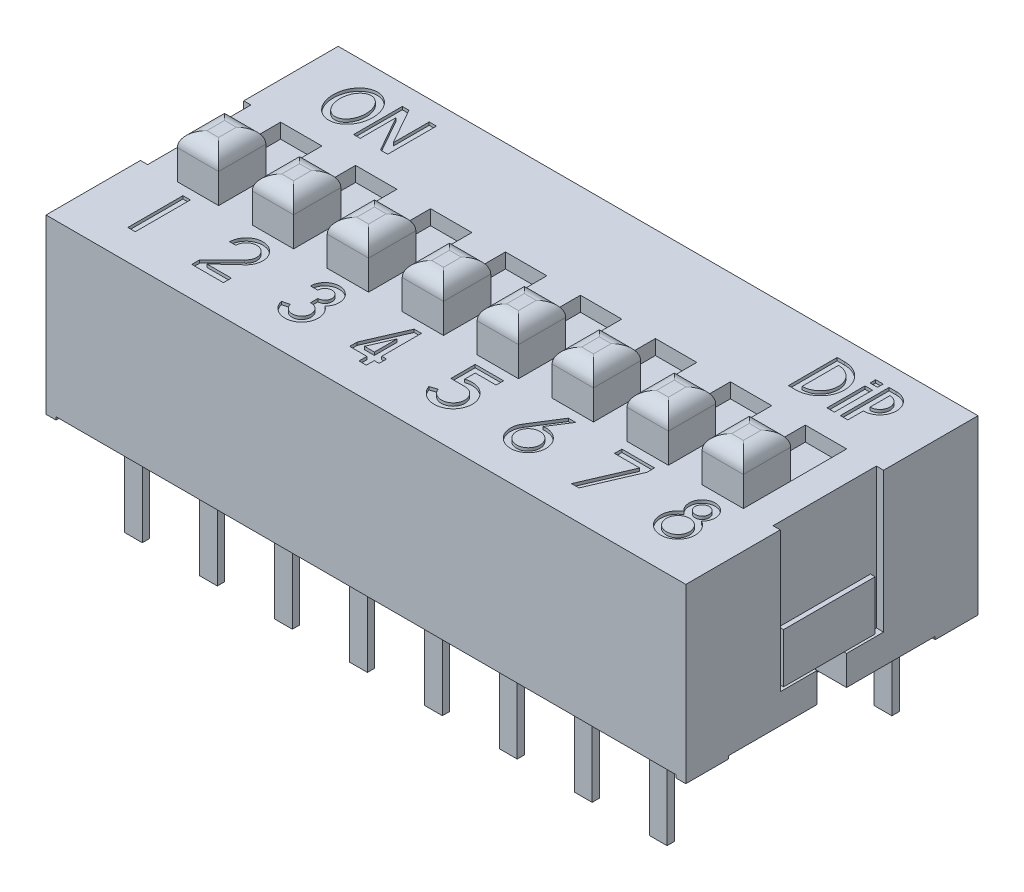
SolidWorks part; units mm, degrees
ref_plane "Front Plane" through (0, 0, 0) normal (0, 0, 1) x (1, 0, 0)
ref_plane "Top Plane" through (0, 0, 0) normal (0, 1, 0) x (1, 0, 0)
ref_plane "Right Plane" through (0, 0, 0) normal (1, 0, 0) x (0, 0, -1)
sketch "Sketch3" plane through (0, 0, 0) normal (0, 1, 0) x (1, 0, 0)
  line L1 (-10.84, 4.95) -> (10.84, 4.95)
  line L2 (-10.84, 4.95) -> (-10.84, -4.95)
  line L3 (-10.84, -4.95) -> (10.84, -4.95)
  line L4 (10.84, 4.95) -> (10.84, -4.95)
  line L5 (-10.84, 4.95) -> (10.84, -4.95) construction
  line L6 (-10.84, -4.95) -> (10.84, 4.95) construction
  point P0 (0, 0)
  dimension "D1" = 21.68
  dimension "D2" = 9.9
extrude "Boss-Extrude2" add sketch "Sketch3" against normal blind 5.85
sketch "Sketch4" plane through (0, 0, 4.95) normal (0, 0, 1) x (1, 0, 0)
  line L0 (-10.84, -5.85) -> (10.84, -5.85) construction
  line L1 (-10.5, -5.75) -> (10.5, -5.75)
  line L2 (-10.5, -5.75) -> (-10.5, -5.95)
  line L3 (-10.5, -5.95) -> (10.5, -5.95)
  line L4 (10.5, -5.75) -> (10.5, -5.95)
  line L5 (-10.5, -5.75) -> (10.5, -5.95) construction
  line L6 (-10.5, -5.95) -> (10.5, -5.75) construction
  point P0 (0, -5.85)
  dimension "D1" = 0.2
  dimension "D2" = 21
extrude "Cut-Extrude2" cut sketch "Sketch4" against normal blind 10
sketch "Sketch5" plane through (-10.84, 0, 0) normal (-1, 0, 0) x (0, 0, 1)
  line L0 (-4.95, -5.85) -> (4.95, -5.85) construction
  line L1 (-3.5, -5.75) -> (3.5, -5.75)
  line L2 (-3.5, -5.75) -> (-3.5, -5.95)
  line L3 (-3.5, -5.95) -> (3.5, -5.95)
  line L4 (3.5, -5.75) -> (3.5, -5.95)
  line L5 (-3.5, -5.75) -> (3.5, -5.95) construction
  line L6 (-3.5, -5.95) -> (3.5, -5.75) construction
  point P0 (0, -5.85)
  dimension "D1" = 0.2
  dimension "D2" = 7
extrude "Cut-Extrude3" cut sketch "Sketch5" against normal blind 22
sketch "Sketch6" plane through (0, 0, 0) normal (0, 1, 0) x (1, 0, 0)
  line L0 (-10.84, 4.95) -> (-10.84, -4.95) construction
  line L1 (-11.0837, 1.75) -> (-10.5963, 1.75)
  line L2 (-11.0837, 1.75) -> (-11.0837, -1.75)
  line L3 (-11.0837, -1.75) -> (-10.5963, -1.75)
  line L4 (-10.5963, 1.75) -> (-10.5963, -1.75)
  line L5 (-11.0837, 1.75) -> (-10.5963, -1.75) construction
  line L6 (-11.0837, -1.75) -> (-10.5963, 1.75) construction
  line L7 (0, 4.95) -> (0, -4.95) construction
  line L8 (10.84, 4.95) -> (-10.84, 4.95) construction
  line L9 (-10.84, -4.95) -> (10.84, -4.95) construction
  line L10 (11.0837, -1.75) -> (10.5963, 1.75) construction
  line L11 (11.0837, 1.75) -> (10.5963, -1.75) construction
  line L12 (10.5963, 1.75) -> (10.5963, -1.75)
  line L13 (11.0837, -1.75) -> (10.5963, -1.75)
  line L14 (11.0837, 1.75) -> (11.0837, -1.75)
  line L15 (11.0837, 1.75) -> (10.5963, 1.75)
  point P0 (-10.84, 0)
  point P17 (10.84, 0)
  dimension "D1" = 3.5
extrude "Cut-Extrude4" cut sketch "Sketch6" against normal blind 4.75
sketch "Sketch7" plane through (-10.84, 0, 0) normal (-1, 0, 0) x (0, 0, 1)
  line L0 (1.75, -4.75) -> (-1.75, -4.75) construction
  line L1 (0.4994, -4.75) -> (-0.4963, -4.75)
  line L2 (0.4994, -4.75) -> (0.4994, -5.75)
  line L3 (0.4994, -5.75) -> (-0.4963, -5.75)
  line L4 (-0.4963, -4.75) -> (-0.4963, -5.75)
  line L5 (3.5, -5.75) -> (-3.5, -5.75) construction
extrude "Cut-Extrude5" cut sketch "Sketch7" against normal blind 22
sketch "Sketch8" plane through (-10.5963, 0, 0) normal (-1, 0, 0) x (0, 0, 1)
  line L0 (1.75, -4.75) -> (0.4994, -4.75) construction
  line L1 (1.55, -4.75) -> (-1.55, -4.75)
  line L2 (1.55, -4.75) -> (1.55, -3.0694)
  line L3 (1.55, -3.0694) -> (-1.55, -3.0694)
  line L4 (-1.55, -4.75) -> (-1.55, -3.0694)
  line L5 (-1.75, 0) -> (-1.75, -4.75) construction
  line L6 (1.75, -4.75) -> (1.75, 0) construction
  dimension "D1" = 0.2
  dimension "D2" = 0.2
extrude "Boss-Extrude3" add sketch "Sketch8" along normal blind 0.15 and the other way blind 21.35
sketch "Sketch9" plane through (0, 0, 0) normal (0, 1, 0) x (1, 0, 0)
  line L0 (-10.84, 4.95) -> (-10.84, 1.75) construction
  line L1 (-9.59, 1.75) -> (-8.19, 1.75)
  line L2 (-9.59, 1.75) -> (-9.59, -1.75)
  line L3 (-9.59, -1.75) -> (-8.19, -1.75)
  line L4 (-8.19, 1.75) -> (-8.19, -1.75)
  line L5 (-9.59, 1.75) -> (-8.19, -1.75) construction
  line L6 (-9.59, -1.75) -> (-8.19, 1.75) construction
  line L7 (0, 4.95) -> (0, -4.95) construction
  line L8 (-7.0506, 1.75) -> (-5.6494, 1.75)
  line L9 (-7.0506, 1.75) -> (-7.0506, -1.75)
  line L10 (-7.0506, -1.75) -> (-5.6494, -1.75)
  line L11 (-5.6494, 1.75) -> (-5.6494, -1.75)
  line L12 (-7.0506, 1.75) -> (-5.6494, -1.75) construction
  line L13 (-7.0506, -1.75) -> (-5.6494, 1.75) construction
  line L14 (-4.5106, 1.75) -> (-3.1094, 1.75)
  line L15 (-4.5106, 1.75) -> (-4.5106, -1.75)
  line L16 (-4.5106, -1.75) -> (-3.1094, -1.75)
  line L17 (-3.1094, 1.75) -> (-3.1094, -1.75)
  line L18 (-4.5106, 1.75) -> (-3.1094, -1.75) construction
  line L19 (-4.5106, -1.75) -> (-3.1094, 1.75) construction
  line L20 (-1.9706, 1.75) -> (-0.5694, 1.75)
  line L21 (-1.9706, 1.75) -> (-1.9706, -1.75)
  line L22 (-1.9706, -1.75) -> (-0.5694, -1.75)
  line L23 (-0.5694, 1.75) -> (-0.5694, -1.75)
  line L24 (-1.9706, 1.75) -> (-0.5694, -1.75) construction
  line L25 (-1.9706, -1.75) -> (-0.5694, 1.75) construction
  line L26 (10.84, 4.95) -> (-10.84, 4.95) construction
  line L27 (-10.84, -4.95) -> (10.84, -4.95) construction
  line L28 (1.9706, -1.75) -> (0.5694, 1.75) construction
  line L29 (1.9706, 1.75) -> (0.5694, -1.75) construction
  line L30 (4.5106, -1.75) -> (3.1094, 1.75) construction
  line L31 (4.5106, 1.75) -> (3.1094, -1.75) construction
  line L32 (7.0506, -1.75) -> (5.6494, 1.75) construction
  line L33 (7.0506, 1.75) -> (5.6494, -1.75) construction
  line L34 (9.59, -1.75) -> (8.19, 1.75) construction
  line L35 (9.59, 1.75) -> (8.19, -1.75) construction
  line L36 (0.5694, 1.75) -> (0.5694, -1.75)
  line L37 (1.9706, -1.75) -> (0.5694, -1.75)
  line L38 (1.9706, 1.75) -> (1.9706, -1.75)
  line L39 (1.9706, 1.75) -> (0.5694, 1.75)
  line L40 (3.1094, 1.75) -> (3.1094, -1.75)
  line L41 (4.5106, -1.75) -> (3.1094, -1.75)
  line L42 (4.5106, 1.75) -> (4.5106, -1.75)
  line L43 (4.5106, 1.75) -> (3.1094, 1.75)
  line L44 (5.6494, 1.75) -> (5.6494, -1.75)
  line L45 (7.0506, -1.75) -> (5.6494, -1.75)
  line L46 (7.0506, 1.75) -> (7.0506, -1.75)
  line L47 (7.0506, 1.75) -> (5.6494, 1.75)
  line L48 (8.19, 1.75) -> (8.19, -1.75)
  line L49 (9.59, -1.75) -> (8.19, -1.75)
  line L50 (9.59, 1.75) -> (9.59, -1.75)
  line L51 (9.59, 1.75) -> (8.19, 1.75)
  point P0 (-8.89, 0)
  point P7 (-6.35, 0)
  point P13 (-3.81, 0)
  point P18 (-1.27, 0)
  point P45 (1.27, 0)
  point P46 (3.81, 0)
  point P47 (6.35, 0)
  point P48 (8.89, 0)
  dimension "D1" = 1.4
  dimension "D2" = 3.5
  dimension "D3" = 1.95
  dimension "D4" = 2.54
  dimension "D5" = 2.54
  dimension "D6" = 2.54
extrude "Cut-Extrude6" cut sketch "Sketch9" against normal blind 0.5
sketch "Sketch12" plane through (0, -0.5, 0) normal (0, 1, 0) x (1, 0, 0)
  line L0 (-9.59, 1.75) -> (-9.59, -1.75) construction
  line L1 (-8.19, -1.75) -> (-9.59, -1.75)
  line L2 (-8.19, -1.75) -> (-8.19, -0.15)
  line L3 (-8.19, -0.15) -> (-9.59, -0.15)
  line L4 (-9.59, -1.75) -> (-9.59, -0.15)
  line L5 (-7.0506, 1.75) -> (-7.0506, -1.75) construction
  line L6 (-5.6494, -1.75) -> (-7.0506, -1.75)
  line L7 (-5.6494, -1.75) -> (-5.6494, -0.15)
  line L8 (-5.6494, -0.15) -> (-7.0506, -0.15)
  line L9 (-7.0506, -1.75) -> (-7.0506, -0.15)
  line L10 (-4.5106, 1.75) -> (-4.5106, -1.75) construction
  line L11 (-3.1094, -1.75) -> (-4.5106, -1.75)
  line L12 (-3.1094, -1.75) -> (-3.1094, -0.15)
  line L13 (-3.1094, -0.15) -> (-4.5106, -0.15)
  line L14 (-4.5106, -1.75) -> (-4.5106, -0.15)
  line L15 (-1.9706, 1.75) -> (-1.9706, -1.75) construction
  line L16 (-1.9706, -0.15) -> (-0.5694, -0.15)
  line L17 (-1.9706, -0.15) -> (-1.9706, -1.75)
  line L18 (-1.9706, -1.75) -> (-0.5694, -1.75)
  line L19 (-0.5694, -0.15) -> (-0.5694, -1.75)
  line L20 (0.5694, 1.75) -> (0.5694, -1.75) construction
  line L21 (1.9706, -1.75) -> (0.5694, -1.75)
  line L22 (1.9706, -1.75) -> (1.9706, -0.15)
  line L23 (1.9706, -0.15) -> (0.5694, -0.15)
  line L24 (0.5694, -1.75) -> (0.5694, -0.15)
  line L25 (3.1094, 1.75) -> (3.1094, -1.75) construction
  line L26 (4.5106, -1.75) -> (3.1094, -1.75)
  line L27 (4.5106, -1.75) -> (4.5106, -0.15)
  line L28 (4.5106, -0.15) -> (3.1094, -0.15)
  line L29 (3.1094, -1.75) -> (3.1094, -0.15)
  line L30 (5.6494, 1.75) -> (5.6494, -1.75) construction
  line L31 (7.0506, -1.75) -> (5.6494, -1.75)
  line L32 (7.0506, -1.75) -> (7.0506, -0.15)
  line L33 (7.0506, -0.15) -> (5.6494, -0.15)
  line L34 (5.6494, -1.75) -> (5.6494, -0.15)
  line L35 (8.19, 1.75) -> (8.19, -1.75) construction
  line L36 (9.59, -1.75) -> (8.19, -1.75)
  line L37 (9.59, -1.75) -> (9.59, -0.15)
  line L38 (9.59, -0.15) -> (8.19, -0.15)
  line L39 (8.19, -1.75) -> (8.19, -0.15)
  dimension "D1" = 1.6
extrude "Boss-Extrude4" add sketch "Sketch12" along normal blind 2
fillet "Fillet1" radius 0.5 32 edges at (8.89, 1.5, 1.75) (8.19, 1.5, 0.95) (8.89, 1.5, 0.15) (9.59, 1.5, 0.95) (6.35, 1.5, 1.75) (5.6494, 1.5, 0.95) (6.35, 1.5, 0.15) (7.0506, 1.5, 0.95) (3.81, 1.5, 1.75) (3.1094, 1.5, 0.95) (3.81, 1.5, 0.15) (4.5106, 1.5, 0.95) (1.27, 1.5, 1.75) (0.5694, 1.5, 0.95) (1.27, 1.5, 0.15) (1.9706, 1.5, 0.95) (-1.27, 1.5, 0.15) (-0.5694, 1.5, 0.95) (-1.27, 1.5, 1.75) (-1.9706, 1.5, 0.95) (-3.81, 1.5, 1.75) (-4.5106, 1.5, 0.95) (-3.81, 1.5, 0.15) (-3.1094, 1.5, 0.95) (-6.35, 1.5, 1.75) (-7.0506, 1.5, 0.95) (-6.35, 1.5, 0.15) (-5.6494, 1.5, 0.95) (-8.89, 1.5, 1.75) (-9.59, 1.5, 0.95) (-8.89, 1.5, 0.15) (-8.19, 1.5, 0.95)
sketch "Sketch13" plane through (0, -5.75, 0) normal (0, -1, 0) x (1, 0, 0)
  line L0 (-10.84, 3.5) -> (-10.84, 4.95) construction
  line L1 (-9.19, 3.9365) -> (-8.59, 3.9365)
  line L2 (-9.19, 3.9365) -> (-9.19, 3.6865)
  line L3 (-9.19, 3.6865) -> (-8.59, 3.6865)
  line L4 (-8.59, 3.9365) -> (-8.59, 3.6865)
  line L5 (-9.19, 3.9365) -> (-8.59, 3.6865) construction
  line L6 (-9.19, 3.6865) -> (-8.59, 3.9365) construction
  line L7 (0, 4.95) -> (0, -4.95) construction
  line L8 (-6.65, 3.9344) -> (-6.05, 3.9344)
  line L9 (-6.65, 3.9344) -> (-6.65, 3.6887)
  line L10 (-6.65, 3.6887) -> (-6.05, 3.6887)
  line L11 (-6.05, 3.9344) -> (-6.05, 3.6887)
  line L12 (-6.65, 3.9344) -> (-6.05, 3.6887) construction
  line L13 (-6.65, 3.6887) -> (-6.05, 3.9344) construction
  line L14 (-4.11, 3.9328) -> (-3.51, 3.9328)
  line L15 (-4.11, 3.9328) -> (-4.11, 3.6903)
  line L16 (-4.11, 3.6903) -> (-3.51, 3.6903)
  line L17 (-3.51, 3.9328) -> (-3.51, 3.6903)
  line L18 (-4.11, 3.9328) -> (-3.51, 3.6903) construction
  line L19 (-4.11, 3.6903) -> (-3.51, 3.9328) construction
  line L20 (-1.57, 3.929) -> (-0.97, 3.929)
  line L21 (-1.57, 3.929) -> (-1.57, 3.694)
  line L22 (-1.57, 3.694) -> (-0.97, 3.694)
  line L23 (-0.97, 3.929) -> (-0.97, 3.694)
  line L24 (-1.57, 3.929) -> (-0.97, 3.694) construction
  line L25 (-1.57, 3.694) -> (-0.97, 3.929) construction
  line L26 (10.5, 4.95) -> (-10.5, 4.95) construction
  line L27 (-10.5, -4.95) -> (10.5, -4.95) construction
  line L28 (-10.7463, 0.0015) -> (10.7537, 0.0015) construction
  line L29 (-10.7463, -0.4963) -> (-10.7463, 0.4994) construction
  line L30 (10.7537, -0.4963) -> (10.7537, 0.4994) construction
  line L31 (-1.57, -3.691) -> (-0.97, -3.926) construction
  line L32 (-1.57, -3.926) -> (-0.97, -3.691) construction
  line L33 (-4.11, -3.6872) -> (-3.51, -3.9297) construction
  line L34 (-4.11, -3.9297) -> (-3.51, -3.6872) construction
  line L35 (-6.65, -3.6856) -> (-6.05, -3.9313) construction
  line L36 (-6.65, -3.9313) -> (-6.05, -3.6856) construction
  line L37 (-9.19, -3.6835) -> (-8.59, -3.9335) construction
  line L38 (-9.19, -3.9335) -> (-8.59, -3.6835) construction
  line L39 (-0.97, -3.926) -> (-0.97, -3.691)
  line L40 (-1.57, -3.691) -> (-0.97, -3.691)
  line L41 (-1.57, -3.926) -> (-1.57, -3.691)
  line L42 (-1.57, -3.926) -> (-0.97, -3.926)
  line L43 (-3.51, -3.9297) -> (-3.51, -3.6872)
  line L44 (-4.11, -3.6872) -> (-3.51, -3.6872)
  line L45 (-4.11, -3.9297) -> (-4.11, -3.6872)
  line L46 (-4.11, -3.9297) -> (-3.51, -3.9297)
  line L47 (-6.05, -3.9313) -> (-6.05, -3.6856)
  line L48 (-6.65, -3.6856) -> (-6.05, -3.6856)
  line L49 (-6.65, -3.9313) -> (-6.65, -3.6856)
  line L50 (-6.65, -3.9313) -> (-6.05, -3.9313)
  line L51 (-8.59, -3.9335) -> (-8.59, -3.6835)
  line L52 (-9.19, -3.6835) -> (-8.59, -3.6835)
  line L53 (-9.19, -3.9335) -> (-9.19, -3.6835)
  line L54 (-9.19, -3.9335) -> (-8.59, -3.9335)
  line L55 (9.19, -3.9335) -> (8.59, -3.6835) construction
  line L56 (9.19, -3.6835) -> (8.59, -3.9335) construction
  line L57 (6.65, -3.9313) -> (6.05, -3.6856) construction
  line L58 (6.65, -3.6856) -> (6.05, -3.9313) construction
  line L59 (4.11, -3.9297) -> (3.51, -3.6872) construction
  line L60 (4.11, -3.6872) -> (3.51, -3.9297) construction
  line L61 (1.57, -3.926) -> (0.97, -3.691) construction
  line L62 (1.57, -3.691) -> (0.97, -3.926) construction
  line L63 (1.57, 3.694) -> (0.97, 3.929) construction
  line L64 (1.57, 3.929) -> (0.97, 3.694) construction
  line L65 (4.11, 3.6903) -> (3.51, 3.9328) construction
  line L66 (4.11, 3.9328) -> (3.51, 3.6903) construction
  line L67 (6.65, 3.6887) -> (6.05, 3.9344) construction
  line L68 (6.65, 3.9344) -> (6.05, 3.6887) construction
  line L69 (9.19, 3.6865) -> (8.59, 3.9365) construction
  line L70 (9.19, 3.9365) -> (8.59, 3.6865) construction
  line L71 (9.19, -3.9335) -> (8.59, -3.9335)
  line L72 (9.19, -3.9335) -> (9.19, -3.6835)
  line L73 (9.19, -3.6835) -> (8.59, -3.6835)
  line L74 (8.59, -3.9335) -> (8.59, -3.6835)
  line L75 (6.65, -3.9313) -> (6.05, -3.9313)
  line L76 (6.65, -3.9313) -> (6.65, -3.6856)
  line L77 (6.65, -3.6856) -> (6.05, -3.6856)
  line L78 (6.05, -3.9313) -> (6.05, -3.6856)
  line L79 (4.11, -3.9297) -> (3.51, -3.9297)
  line L80 (4.11, -3.9297) -> (4.11, -3.6872)
  line L81 (4.11, -3.6872) -> (3.51, -3.6872)
  line L82 (3.51, -3.9297) -> (3.51, -3.6872)
  line L83 (1.57, -3.926) -> (0.97, -3.926)
  line L84 (1.57, -3.926) -> (1.57, -3.691)
  line L85 (1.57, -3.691) -> (0.97, -3.691)
  line L86 (0.97, -3.926) -> (0.97, -3.691)
  line L87 (0.97, 3.929) -> (0.97, 3.694)
  line L88 (1.57, 3.694) -> (0.97, 3.694)
  line L89 (1.57, 3.929) -> (1.57, 3.694)
  line L90 (1.57, 3.929) -> (0.97, 3.929)
  line L91 (3.51, 3.9328) -> (3.51, 3.6903)
  line L92 (4.11, 3.6903) -> (3.51, 3.6903)
  line L93 (4.11, 3.9328) -> (4.11, 3.6903)
  line L94 (4.11, 3.9328) -> (3.51, 3.9328)
  line L95 (6.05, 3.9344) -> (6.05, 3.6887)
  line L96 (6.65, 3.6887) -> (6.05, 3.6887)
  line L97 (6.65, 3.9344) -> (6.65, 3.6887)
  line L98 (6.65, 3.9344) -> (6.05, 3.9344)
  line L99 (8.59, 3.9365) -> (8.59, 3.6865)
  line L100 (9.19, 3.6865) -> (8.59, 3.6865)
  line L101 (9.19, 3.9365) -> (9.19, 3.6865)
  line L102 (9.19, 3.9365) -> (8.59, 3.9365)
  point P0 (-8.89, 3.8115)
  point P7 (-6.35, 3.8115)
  point P12 (-3.81, 3.8115)
  point P17 (-1.27, 3.8115)
  point P50 (-1.27, -3.8085)
  point P51 (-3.81, -3.8085)
  point P52 (-6.35, -3.8085)
  point P53 (-8.89, -3.8085)
  point P86 (8.89, -3.8085)
  point P87 (6.35, -3.8085)
  point P88 (3.81, -3.8085)
  point P89 (1.27, -3.8085)
  point P90 (1.27, 3.8115)
  point P91 (3.81, 3.8115)
  point P92 (6.35, 3.8115)
  point P93 (8.89, 3.8115)
  dimension "D1" = 0.6
  dimension "D2" = 0.25
  dimension "D3" = 1.95
  dimension "D4" = 0.6
  dimension "D5" = 2.54
  dimension "D6" = 0.6
  dimension "D7" = 2.54
  dimension "D8" = 0.6
  dimension "D9" = 2.54
  dimension "D10" = 3.81
  dimension "D11" = 3.81
  dimension "D12" = 3.81
  dimension "D13" = 3.81
extrude "Boss-Extrude5" add sketch "Sketch13" along normal blind 3.25
sketch "Sketch14" plane through (0, 0, 0) normal (0, 1, 0) x (1, 0, 0)
  ellipse E0 centre (-8.8336, 3.447) end of major axis (-8.8336, 2.6213) minor radius 0.6721
  ellipse E1 centre (-8.8336, 3.447) end of major axis (-8.8336, 2.8325) minor radius 0.4417
extrude "Cut-Extrude7" cut sketch "Sketch14" against normal blind 0.1
sketch "Sketch15" plane through (0, 0, 0) normal (0, 1, 0) x (1, 0, 0)
  line L0 (-8.8336, 4.2728) -> (10.84, 4.2728) construction
  line L1 (10.84, 1.75) -> (10.84, 4.95) construction
  line L2 (-8.8336, 2.6213) -> (10.84, 2.6213) construction
  line L3 (-7.7652, 4.2728) -> (-7.0782, 3.0559)
  line L4 (-7.9895, 2.6213) -> (-7.7652, 2.6213)
  line L5 (-7.9895, 2.6213) -> (-7.9895, 4.2728)
  line L7 (-7.7652, 2.6213) -> (-7.7652, 3.8382)
  line L8 (-7.0782, 2.6213) -> (-6.8329, 2.6213)
  line L9 (-7.0782, 3.0559) -> (-7.0782, 4.2728)
  line L10 (-7.0782, 4.2728) -> (-6.8329, 4.2728)
  line L11 (-6.8329, 2.6213) -> (-6.8329, 4.2728)
  line L12 (-7.7652, 4.2728) -> (-8.0105, 4.2728)
  line L14 (-8.0105, 4.2728) -> (-7.9895, 4.2355)
  line L15 (-7.7652, 3.8382) -> (-7.0782, 2.6213)
  ellipse E0 centre (-8.8336, 3.447) end of major axis (-8.8336, 2.6213) minor radius 0.6721 construction
  ellipse E1 centre (-8.8336, 3.447) end of major axis (-8.8336, 2.6213) minor radius 0.6721 construction
extrude "Cut-Extrude8" cut sketch "Sketch15" against normal blind 0.1 contours L7 L15 L8 L11 L10 L9 L3 L12 L5 L4
sketch "Sketch16" plane through (0, 0, 0) normal (0, 1, 0) x (1, 0, 0)
  line L0 (-6.8329, 4.2728) -> (10.84, 4.2728) construction
  line L1 (10.84, 1.75) -> (10.84, 4.95) construction
  line L2 (-6.8329, 2.6213) -> (10.84, 2.6213) construction
  line L3 (8.5039, 2.6213) -> (8.5039, 4.2728)
  line L4 (8.5039, 4.2728) -> (8.7584, 4.2728)
  line L5 (8.7584, 4.0464) -> (8.7584, 3.5762)
  line L6 (8.7584, 2.6213) -> (8.5039, 2.6213)
  line L7 (8.7584, 3.3779) -> (8.7584, 3.3735)
  line L8 (8.7584, 3.3779) -> (8.7584, 3.5762)
  line L9 (8.3035, 2.6213) -> (8.0502, 2.6213)
  line L10 (8.3035, 2.6213) -> (8.3035, 3.9113)
  line L11 (8.3035, 3.9113) -> (8.0502, 3.9113)
  line L12 (8.0502, 2.6213) -> (8.0502, 3.9113)
  line L13 (8.0502, 4.2728) -> (8.3035, 4.2728)
  line L14 (8.0502, 4.2728) -> (8.0502, 4.0811)
  line L15 (8.0502, 4.0811) -> (8.3035, 4.0811)
  line L16 (8.3035, 4.2728) -> (8.3035, 4.0811)
  line L17 (6.9987, 2.6213) -> (6.7448, 2.6213)
  line L18 (6.9987, 2.8305) -> (6.9987, 4.0636)
  line L19 (6.9987, 4.2728) -> (6.7448, 4.2728)
  line L20 (6.7448, 2.6213) -> (6.7448, 4.2728)
  line L22 (8.7584, 3.1467) -> (8.7584, 2.6213)
  arc A0 (8.7584, 3.1467) -> (8.7359, 4.2728) centre (8.7584, 3.7099) ccw
  arc A1 (8.7584, 3.3735) -> (8.7584, 4.0464) centre (8.7584, 3.7099) ccw
  arc A2 (6.9987, 2.6213) -> (6.9987, 4.2728) centre (6.9987, 3.447) ccw
  arc A3 (6.9987, 2.8305) -> (6.9987, 4.0636) centre (6.9987, 3.447) ccw
extrude "Cut-Extrude11" cut sketch "Sketch16" against normal blind 0.1
sketch "Sketch17" plane through (0, 0, 0) normal (0, 1, 0) x (1, 0, 0)
  line L0 (-8.8359, -2.0624) -> (10.84, -2.0624) construction
  line L1 (-9.0878, -2.0624) -> (-8.8359, -2.0624)
  line L2 (-9.0878, -2.0624) -> (-9.0878, -3.93)
  line L3 (-9.0878, -3.93) -> (-8.8359, -3.93)
  line L4 (-8.8359, -2.0624) -> (-8.8359, -3.93)
  line L5 (-9.0878, -2.0624) -> (-8.8359, -3.93) construction
  line L6 (-9.0878, -3.93) -> (-8.8359, -2.0624) construction
  line L7 (10.84, -4.95) -> (10.84, -1.75) construction
  line L8 (-8.8359, -3.93) -> (10.84, -3.93) construction
  line L9 (-5.8489, -3.93) -> (-5.8489, -3.6621)
  line L10 (-5.8489, -3.6621) -> (-6.6786, -3.6621)
  line L11 (-5.8489, -3.93) -> (-6.9202, -3.93)
  line L12 (-6.9202, -3.93) -> (-6.9202, -3.6609)
  line L13 (-6.6786, -3.6621) -> (-6.0003, -3.0353)
  line L14 (-6.9202, -3.6609) -> (-6.1001, -2.8408)
  line L15 (-6.7361, -2.6233) -> (-6.9419, -2.6233)
  line L16 (-4.0299, -2.5519) -> (-4.2771, -2.5519)
  line L17 (-4.0786, -3.4357) -> (-4.3192, -3.4926)
  line L18 (-3.7828, -3.0416) -> (-3.7852, -2.7943)
  line L19 (-1.2547, -2.0624) -> (-1.8404, -3.4079)
  line L20 (-1.0055, -2.0624) -> (-1.2547, -2.0624)
  line L21 (-1.0055, -2.0624) -> (-1.0055, -3.4079)
  line L22 (-1.0055, -3.93) -> (-1.2547, -3.93)
  line L23 (-1.2547, -2.6345) -> (-1.2547, -3.4079)
  line L24 (-0.8439, -3.6621) -> (-1.0055, -3.6621)
  line L25 (1.0703, -2.3152) -> (1.0703, -2.677)
  line L26 (-0.8439, -3.4079) -> (-1.0055, -3.4079)
  line L27 (-1.8404, -3.6621) -> (-1.8404, -3.4079)
  line L28 (-1.2547, -2.0624) -> (-1.0056, -2.0624)
  line L29 (-1.2547, -3.6621) -> (-1.2547, -3.93)
  line L30 (-1.2547, -2.6345) -> (-1.5913, -3.4079)
  line L31 (-1.2547, -3.4079) -> (-1.5913, -3.4079)
  line L32 (-1.2547, -3.6621) -> (-1.8404, -3.6621)
  line L33 (-1.0055, -3.6621) -> (-1.0055, -3.93)
  line L34 (-0.8439, -3.4079) -> (-0.8439, -3.6621)
  line L35 (1.7781, -2.0624) -> (0.8154, -2.0624)
  line L36 (1.7781, -2.0624) -> (1.7781, -2.3152)
  line L37 (1.7781, -2.3152) -> (1.0703, -2.3152)
  line L38 (0.8154, -2.0624) -> (0.8154, -2.3152)
  line L39 (0.8154, -2.3152) -> (0.8154, -2.8714)
  line L40 (1.2909, -2.8873) -> (0.8154, -2.8873)
  line L41 (0.8154, -2.8873) -> (0.8154, -2.3152)
  line L42 (0.9168, -3.4163) -> (0.6819, -3.4994)
  line L43 (3.7877, -2.7359) -> (4.2229, -2.0624)
  line L44 (4.2229, -2.0624) -> (3.9704, -2.0624)
  line L45 (3.9704, -2.0624) -> (3.3739, -3.0089)
  line L46 (6.8923, -2.3152) -> (6.1975, -3.93)
  line L47 (5.7875, -2.0624) -> (6.8923, -2.0624)
  line L48 (5.7875, -2.0624) -> (5.7875, -2.3152)
  line L49 (5.7875, -2.3152) -> (6.6412, -2.3152)
  line L50 (6.8923, -2.0624) -> (6.8923, -2.3152)
  line L52 (6.1975, -3.93) -> (5.9464, -3.93)
  line L53 (6.6412, -2.3152) -> (5.9464, -3.93)
  arc A0 (-6.0003, -3.0353) -> (-6.9419, -2.6233) centre (-6.3809, -2.6233) ccw
  arc A1 (-6.1634, -2.9041) -> (-6.7361, -2.6233) centre (-6.3809, -2.6233) ccw
  arc A2 (-4.3192, -3.4926) -> (-3.4403, -2.897) centre (-3.7664, -3.362) ccw
  arc A3 (-3.4403, -2.897) -> (-4.2771, -2.5519) centre (-3.7875, -2.5519) ccw
  arc A4 (-4.0786, -3.4357) -> (-3.7828, -3.0416) centre (-3.7664, -3.362) ccw
  arc A5 (-3.7852, -2.7943) -> (-4.0299, -2.5519) centre (-3.7875, -2.5519) ccw
  arc A6 (0.6819, -3.4994) -> (1.0703, -2.677) centre (1.2909, -3.2841) ccw
  arc A7 (0.9168, -3.4163) -> (1.2909, -2.8873) centre (1.2909, -3.2841) ccw
  arc A8 (3.3739, -3.0089) -> (3.7877, -2.7359) centre (3.8821, -3.3292) ccw
  circle A9 centre (3.8821, -3.3292) radius 0.3967
  arc A10 (8.6576, -2.8375) -> (9.2521, -2.8262) centre (8.9644, -3.3406) ccw
  circle A11 centre (8.9644, -3.3406) radius 0.394
  arc A12 (9.2521, -2.8262) -> (8.6576, -2.8375) centre (8.9487, -2.5046) ccw
  circle A13 centre (8.9487, -2.5046) radius 0.2366
  point P0 (-8.9619, -2.9962)
extrude "Cut-Extrude12" cut sketch "Sketch17" against normal blind 0.1 contours A1 L14 L12 L11 L9 L10 L13 A0 L15 | A5 L18 A4 L17 A2 A3 L16 | L34 L26 L21 L20 L19 L27 L32 L29 L22 L33 L24 L23 L31 L30 | A7 L42 A6 L25 L37 L36 L35 L38 L39 L41 L40 | L45 A8 L43 L44 A9 | L49 L53 L52 L46 L50 L47 L48 | A10 A12 A13 A11 | L2 L3 L4 L1
